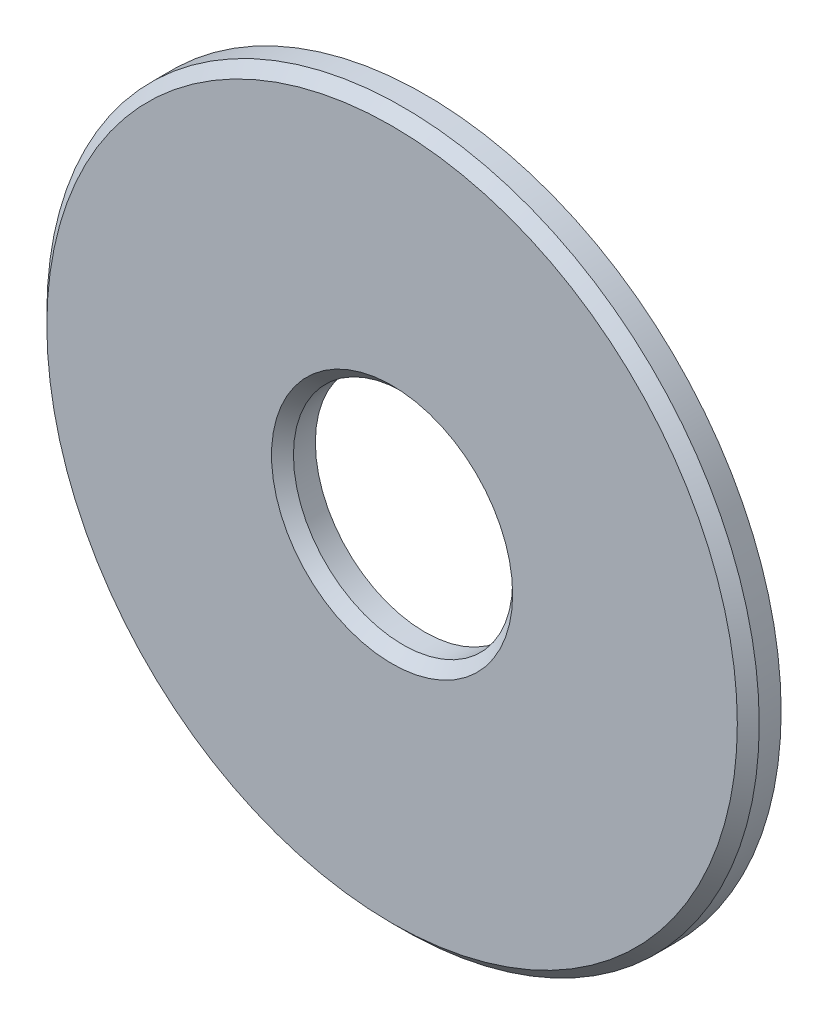
SolidWorks part; units mm, degrees
ref_plane "Ön Düzlem" through (0, 0, 0) normal (0, 0, 1) x (1, 0, 0)
ref_plane "Üst Düzlem" through (0, 0, 0) normal (0, 1, 0) x (1, 0, 0)
ref_plane "Sağ Düzlem" through (0, 0, 0) normal (1, 0, 0) x (0, 0, -1)
sketch "Çizim1" plane through (0, 0, 0) normal (0, 0, 1) x (1, 0, 0)
  circle A0 centre (0, 0) radius 65
  circle A1 centre (0, 0) radius 20
  dimension "D1" = 130
  dimension "D2" = 40
extrude "Yükseklik-Ekstrüzyon1" add sketch "Çizim1" along normal blind 6
chamfer "Pah1" distance 2 angle 45 2 edges at (65, 0, 6) (20, 0, 6)
